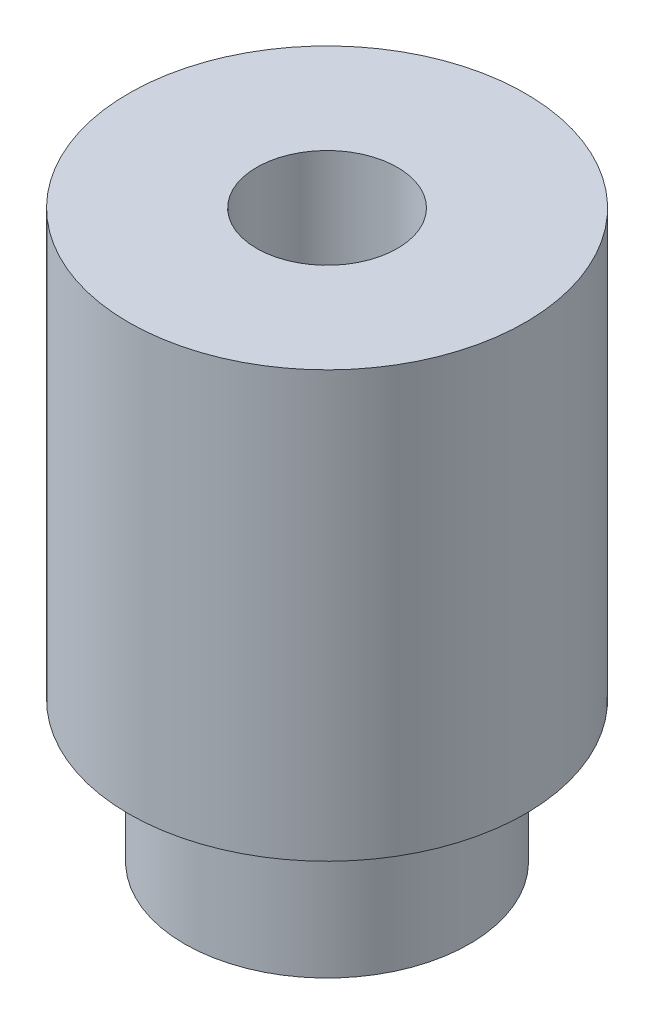
SolidWorks part; units mm, degrees
material "AISI 1020 Steel, Cold Rolled"
ref_plane "Front Plane" through (0, 0, 0) normal (0, 0, 1) x (1, 0, 0)
ref_plane "Top Plane" through (0, 0, 0) normal (0, 1, 0) x (1, 0, 0)
ref_plane "Right Plane" through (0, 0, 0) normal (1, 0, 0) x (0, 0, -1)
sketch "Sketch1" plane through (0, 0, 0) normal (0, 1, 0) x (1, 0, 0)
  circle A0 centre (0, 0) radius 10.033
  dimension "D1" = 20.066
extrude "Boss-Extrude1" add sketch "Sketch1" along normal blind 9.906
sketch "Sketch2" plane through (0, 9.906, 0) normal (0, 1, 0) x (1, 0, 0)
  circle A0 centre (0, 0) radius 13.97
  dimension "D1" = 27.94
extrude "Boss-Extrude2" add sketch "Sketch2" along normal blind 29.972
sketch "Sketch3" plane through (0, 39.878, 0) normal (0, 1, 0) x (1, 0, 0)
  circle A0 centre (0, 0) radius 4.953
  dimension "D1" = 9.906
extrude "Cut-Extrude1" cut sketch "Sketch3" against normal through all
